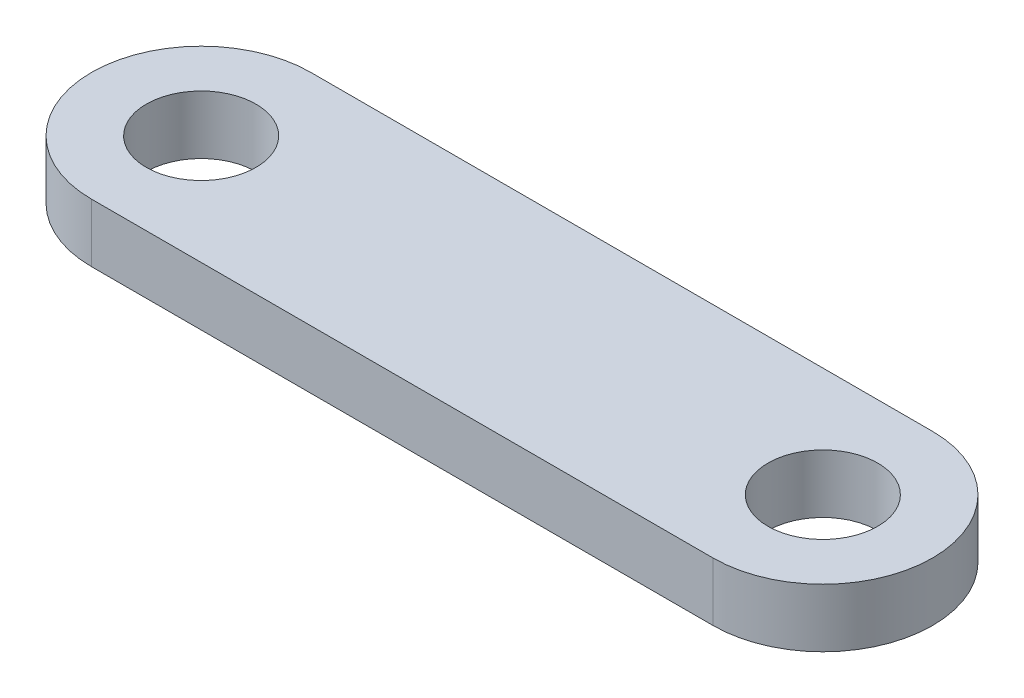
SolidWorks part; units mm, degrees
ref_plane "Front Plane" through (0, 0, 0) normal (0, 0, 1) x (1, 0, 0)
ref_plane "Top Plane" through (0, 0, 0) normal (0, 1, 0) x (1, 0, 0)
ref_plane "Right Plane" through (0, 0, 0) normal (1, 0, 0) x (0, 0, -1)
sketch "Sketch1" plane through (0, 0, 0) normal (0, 1, 0) x (1, 0, 0)
  line L0 (28.3044, 0) -> (-36.2147, 0) construction
  line L1 (-107.95, 19.05) -> (0, 19.05)
  line L2 (-107.95, -19.05) -> (0, -19.05)
  line L3 (-36.2147, 0) -> (-83.8536, 0) construction
  arc A0 (0, -19.05) -> (0, 19.05) centre (0, 0) ccw
  arc A1 (-107.95, 19.05) -> (-107.95, -19.05) centre (-107.95, 0) ccw
  circle A2 centre (-107.95, 0) radius 9.525
  circle A3 centre (0, 0) radius 9.525
  dimension "D1" = 19.05
  dimension "D2" = 19.05
  dimension "D3" = 19.05
  dimension "D4" = 19.05
  dimension "D5" = 107.95
extrude "Boss-Extrude1" add sketch "Sketch1" along normal blind 10.16
